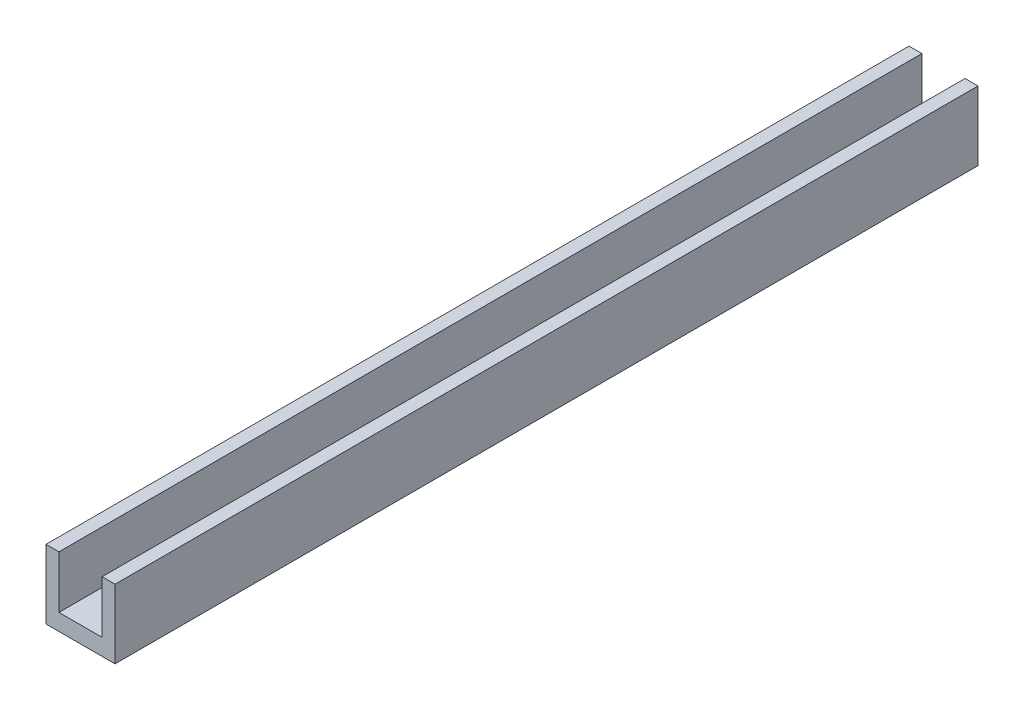
SolidWorks part; units mm, degrees
ref_plane "Front Plane" through (0, 0, 0) normal (0, 0, 1) x (1, 0, 0)
ref_plane "Top Plane" through (0, 0, 0) normal (0, 1, 0) x (1, 0, 0)
ref_plane "Right Plane" through (0, 0, 0) normal (1, 0, 0) x (0, 0, -1)
sketch "Sketch2" plane through (0, 0, 0) normal (0, 0, 1) x (1, 0, 0)
  line L1 (0, 80) -> (80, 80)
  line L2 (0, 80) -> (0, 0)
  line L3 (0, 0) -> (80, 0)
  line L4 (80, 80) -> (80, 0)
  line L5 (0, 80) -> (80, 0) construction
  line L6 (0, 0) -> (80, 80) construction
  point P0 (40, 40)
  point P5 (0, 0)
  point P6 (0, 0)
  point P8 (0, 0)
  point P10 (0, 0)
  dimension "D1" = 40
extrude "Boss-Extrude1" add sketch "Sketch2" along normal blind 1000
sketch "Sketch3" plane through (0, 0, 1000) normal (0, 0, 1) x (1, 0, 0)
  line L0 (80, 80) -> (0, 80) construction
  line L1 (15, 80) -> (65, 80)
  line L2 (15, 80) -> (15, 19.1659)
  line L3 (15, 19.1659) -> (65, 19.1659)
  line L4 (65, 80) -> (65, 19.1659)
  line L5 (0, 80) -> (0, 0) construction
  line L6 (80, 0) -> (80, 80) construction
  dimension "D1" = 15
  dimension "D2" = 15
extrude "Cut-Extrude1" cut sketch "Sketch3" against normal blind 1000
